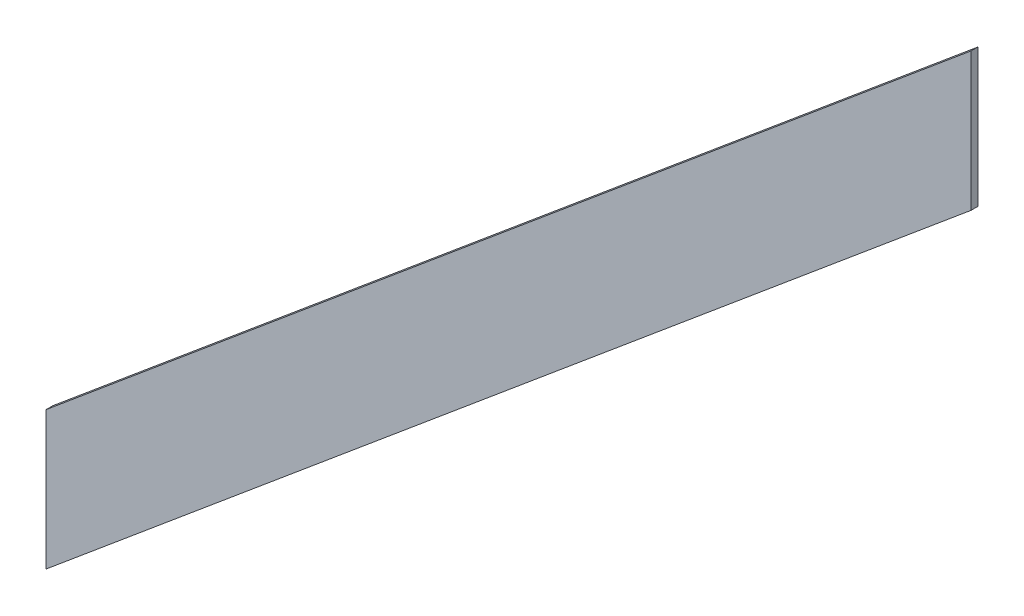
SolidWorks part; units mm, degrees
ref_plane "Front Plane" through (0, 0, 0) normal (0, 0, 1) x (1, 0, 0)
ref_plane "Top Plane" through (0, 0, 0) normal (0, 1, 0) x (1, 0, 0)
ref_plane "Right Plane" through (0, 0, 0) normal (1, 0, 0) x (0, 0, -1)
sketch "Sketch1" plane through (0, 0, 0) normal (0, 0, 1) x (1, 0, 0)
  line L0 (-310.6331, -266.8413) -> (359.3669, 293.1587)
  line L1 (359.3669, 393.1587) -> (-310.6331, -166.8413)
  line L2 (-484.5544, -266.8413) -> (-310.6331, -266.8413)
  line L3 (-484.5544, -266.8413) -> (-484.5544, 393.1587)
  line L4 (-484.5544, 393.1587) -> (-310.6331, 393.1587)
  line L5 (-310.6331, -266.8413) -> (-310.6331, 393.1587)
  line L6 (533.2881, -266.8413) -> (359.3669, -266.8413)
  line L7 (533.2881, -266.8413) -> (533.2881, 393.1587)
  line L8 (533.2881, 393.1587) -> (359.3669, 393.1587)
  line L9 (359.3669, -266.8413) -> (359.3669, 393.1587)
  line L10 (359.3669, -266.8413) -> (-310.6331, -266.8413)
  point P0 (-32.5768, -229.4904)
  dimension "D1" = 100
  dimension "D2" = 670
  dimension "D3" = 660
extrude "Boss-Extrude2" add sketch "Sketch1" along normal blind 5 contours L0 L9 L1 L5
